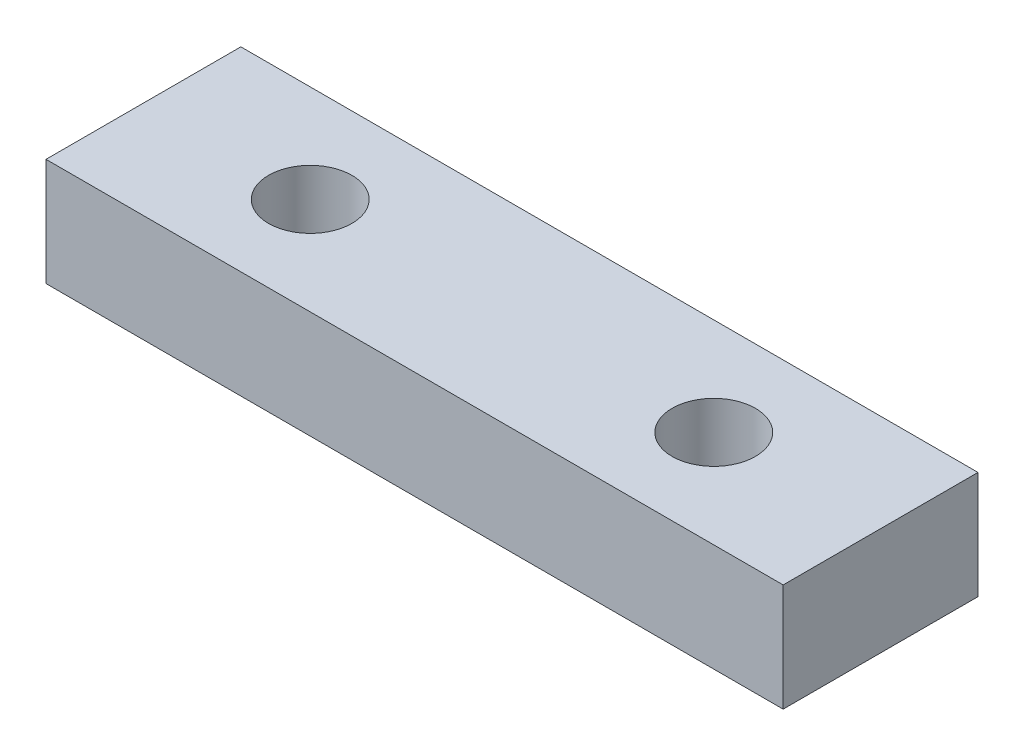
SolidWorks part; units mm, degrees
material "PLA Black"
ref_plane "Front" through (0, 0, 0) normal (0, 0, 1) x (1, 0, 0)
ref_plane "Top" through (0, 0, 0) normal (0, 1, 0) x (1, 0, 0)
ref_plane "Right" through (0, 0, 0) normal (1, 0, 0) x (0, 0, -1)
sketch "Sketch1" plane through (0, 0, 0) normal (0, 1, 0) x (1, 0, 0)
  line L0 (-13.9058, -3.6213) -> (9.3641, -3.6213) construction
  line L1 (0, 6.301) -> (0, -4.9245) construction
  line L2 (13.7, 0) -> (13.7, -7.2425) construction
  line L3 (-13.7, 0) -> (13.7, 0)
  line L4 (-13.7, 0) -> (-13.7, -7.2425)
  line L5 (-13.7, -7.2425) -> (13.7, -7.2425)
  line L6 (13.7, 0) -> (13.7, -7.2425)
  line L7 (-13.7, -7.2425) -> (13.7, -7.2425) construction
  circle A0 centre (7.5, -3.6213) radius 1.55
  circle A1 centre (-7.5, -3.6213) radius 1.55
  dimension "D3" = 3.1
  dimension "D4" = 15
extrude "Boss-Extrude1" add sketch "Sketch1" along normal blind 4 contours L3 L6 L5 L4 | A1 | A0
